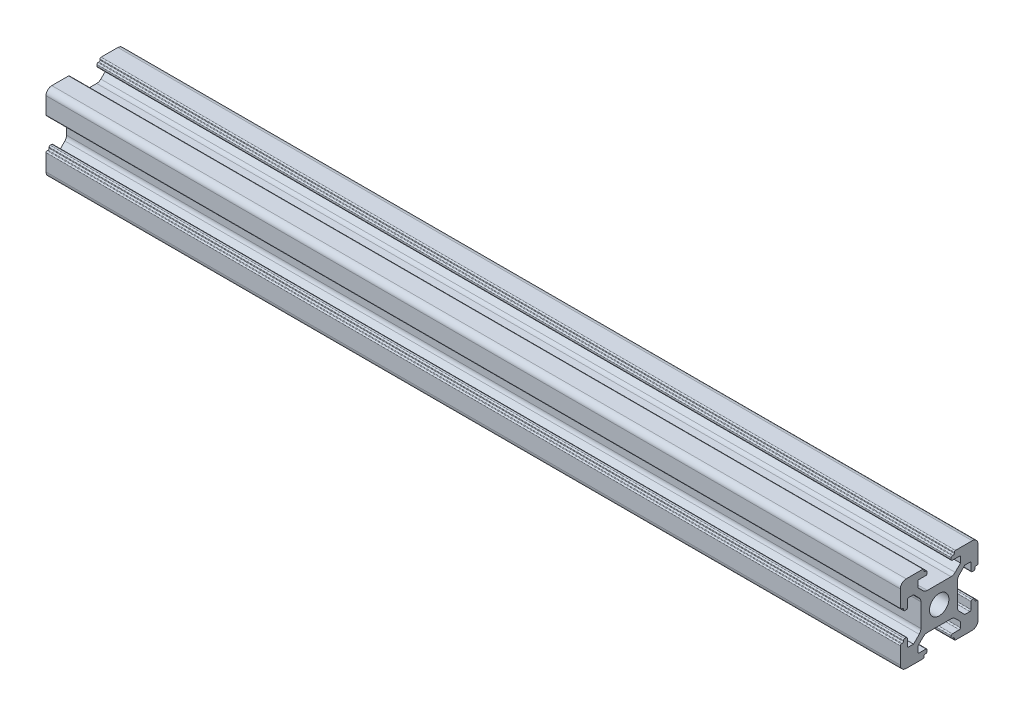
SolidWorks part; units mm, degrees
ref_plane "Front Plane" through (0, 0, 0) normal (0, 0, 1) x (1, 0, 0)
ref_plane "Top Plane" through (0, 0, 0) normal (0, 1, 0) x (1, 0, 0)
ref_plane "Right Plane" through (0, 0, 0) normal (1, 0, 0) x (0, 0, -1)
sketch "Sketch1" plane through (0, 0, 0) normal (1, 0, 0) x (0, 0, -1)
  line L0 (0, 0) -> (0, 50000) construction
  line L1 (0, 0) -> (-50000, 0) construction
  line L2 (10, 4.2) -> (10, 8.5)
  line L3 (9.7, 3.9) -> (9.5, 3.9)
  line L4 (9.2, 3.6) -> (9.2, 3.4)
  line L5 (8.9, 3.1) -> (8.5, 3.1)
  line L6 (8.2, 3.4) -> (8.2, 5.2)
  line L7 (7.9, 5.5) -> (6.6, 5.5)
  line L8 (6.6, 5.5) -> (5.1393, 4.0393)
  line L9 (8.5, 10) -> (4.2, 10)
  line L10 (3.9, 9.7) -> (3.9, 9.5)
  line L11 (3.6, 9.2) -> (3.4, 9.2)
  line L12 (3.1, 8.9) -> (3.1, 8.5)
  line L13 (3.4, 8.2) -> (5.2, 8.2)
  line L14 (5.5, 7.9) -> (5.5, 6.5213)
  line L15 (5.5, 6.5213) -> (4.118, 5.1393)
  line L16 (4.7, 2.9787) -> (4.7, -2.9787)
  line L17 (3.0574, 4.7) -> (-3.0574, 4.7)
  line L18 (-4.7, 2.9787) -> (-4.7, -2.9787)
  line L19 (-5.5, 6.5213) -> (-4.118, 5.1393)
  line L20 (-5.5, 7.9) -> (-5.5, 6.5213)
  line L21 (-3.4, 8.2) -> (-5.2, 8.2)
  line L22 (-3.1, 8.9) -> (-3.1, 8.5)
  line L23 (-3.6, 9.2) -> (-3.4, 9.2)
  line L24 (-3.9, 9.7) -> (-3.9, 9.5)
  line L25 (-8.5, 10) -> (-4.2, 10)
  line L26 (-6.6, 5.5) -> (-5.1393, 4.0393)
  line L27 (-7.9, 5.5) -> (-6.6, 5.5)
  line L28 (-8.2, 3.4) -> (-8.2, 5.2)
  line L29 (-8.9, 3.1) -> (-8.5, 3.1)
  line L30 (-9.2, 3.6) -> (-9.2, 3.4)
  line L31 (-9.7, 3.9) -> (-9.5, 3.9)
  line L32 (-10, 4.2) -> (-10, 8.5)
  line L33 (-10, -4.2) -> (-10, -8.5)
  line L34 (-9.7, -3.9) -> (-9.5, -3.9)
  line L35 (-9.2, -3.6) -> (-9.2, -3.4)
  line L36 (-8.9, -3.1) -> (-8.5, -3.1)
  line L37 (-8.2, -3.4) -> (-8.2, -5.2)
  line L38 (-7.9, -5.5) -> (-6.6, -5.5)
  line L39 (-6.6, -5.5) -> (-5.1393, -4.0393)
  line L40 (-8.5, -10) -> (-4.2, -10)
  line L41 (-3.9, -9.7) -> (-3.9, -9.5)
  line L42 (-3.6, -9.2) -> (-3.4, -9.2)
  line L43 (-3.1, -8.9) -> (-3.1, -8.5)
  line L44 (-3.4, -8.2) -> (-5.2, -8.2)
  line L45 (-5.5, -7.9) -> (-5.5, -6.5213)
  line L46 (-5.5, -6.5213) -> (-4.118, -5.1393)
  line L47 (3.0574, -4.7) -> (-3.0574, -4.7)
  line L48 (5.5, -6.5213) -> (4.118, -5.1393)
  line L49 (5.5, -7.9) -> (5.5, -6.5213)
  line L50 (3.4, -8.2) -> (5.2, -8.2)
  line L51 (3.1, -8.9) -> (3.1, -8.5)
  line L52 (3.6, -9.2) -> (3.4, -9.2)
  line L53 (3.9, -9.7) -> (3.9, -9.5)
  line L54 (8.5, -10) -> (4.2, -10)
  line L55 (6.6, -5.5) -> (5.1393, -4.0393)
  line L56 (7.9, -5.5) -> (6.6, -5.5)
  line L57 (8.2, -3.4) -> (8.2, -5.2)
  line L58 (8.9, -3.1) -> (8.5, -3.1)
  line L59 (9.2, -3.6) -> (9.2, -3.4)
  line L60 (9.7, -3.9) -> (9.5, -3.9)
  line L61 (10, -4.2) -> (10, -8.5)
  circle A0 centre (0, 0) radius 2.5
  arc A1 (10, 8.5) -> (8.5, 10) centre (8.5, 8.5) ccw
  arc A2 (9.7, 3.9) -> (10, 4.2) centre (9.7, 4.2) ccw
  arc A3 (9.5, 3.9) -> (9.2, 3.6) centre (9.5, 3.6) ccw
  arc A4 (9.2, 3.4) -> (8.9, 3.1) centre (8.9, 3.4) cw
  arc A5 (8.5, 3.1) -> (8.2, 3.4) centre (8.5, 3.4) cw
  arc A6 (8.2, 5.2) -> (7.9, 5.5) centre (7.9, 5.2) ccw
  arc A7 (5.2, 8.2) -> (5.5, 7.9) centre (5.2, 7.9) cw
  arc A8 (3.1, 8.5) -> (3.4, 8.2) centre (3.4, 8.5) ccw
  arc A9 (3.4, 9.2) -> (3.1, 8.9) centre (3.4, 8.9) ccw
  arc A10 (4.2, 10) -> (3.9, 9.7) centre (4.2, 9.7) ccw
  arc A11 (3.9, 9.5) -> (3.6, 9.2) centre (3.6, 9.5) cw
  arc A12 (4.7, 2.9787) -> (5.1393, 4.0393) centre (6.2, 2.9787) cw
  arc A13 (3.0574, 4.7) -> (4.118, 5.1393) centre (3.0574, 6.2) ccw
  arc A14 (-3.0574, 4.7) -> (-4.118, 5.1393) centre (-3.0574, 6.2) cw
  arc A15 (-4.7, 2.9787) -> (-5.1393, 4.0393) centre (-6.2, 2.9787) ccw
  arc A16 (-3.9, 9.5) -> (-3.6, 9.2) centre (-3.6, 9.5) ccw
  arc A17 (-4.2, 10) -> (-3.9, 9.7) centre (-4.2, 9.7) cw
  arc A18 (-3.4, 9.2) -> (-3.1, 8.9) centre (-3.4, 8.9) cw
  arc A19 (-3.1, 8.5) -> (-3.4, 8.2) centre (-3.4, 8.5) cw
  arc A20 (-5.2, 8.2) -> (-5.5, 7.9) centre (-5.2, 7.9) ccw
  arc A21 (-8.2, 5.2) -> (-7.9, 5.5) centre (-7.9, 5.2) cw
  arc A22 (-8.5, 3.1) -> (-8.2, 3.4) centre (-8.5, 3.4) ccw
  arc A23 (-9.2, 3.4) -> (-8.9, 3.1) centre (-8.9, 3.4) ccw
  arc A24 (-9.5, 3.9) -> (-9.2, 3.6) centre (-9.5, 3.6) cw
  arc A25 (-9.7, 3.9) -> (-10, 4.2) centre (-9.7, 4.2) cw
  arc A26 (-10, 8.5) -> (-8.5, 10) centre (-8.5, 8.5) cw
  arc A27 (-10, -8.5) -> (-8.5, -10) centre (-8.5, -8.5) ccw
  arc A28 (-9.7, -3.9) -> (-10, -4.2) centre (-9.7, -4.2) ccw
  arc A29 (-9.5, -3.9) -> (-9.2, -3.6) centre (-9.5, -3.6) ccw
  arc A30 (-9.2, -3.4) -> (-8.9, -3.1) centre (-8.9, -3.4) cw
  arc A31 (-8.5, -3.1) -> (-8.2, -3.4) centre (-8.5, -3.4) cw
  arc A32 (-8.2, -5.2) -> (-7.9, -5.5) centre (-7.9, -5.2) ccw
  arc A33 (-5.2, -8.2) -> (-5.5, -7.9) centre (-5.2, -7.9) cw
  arc A34 (-3.1, -8.5) -> (-3.4, -8.2) centre (-3.4, -8.5) ccw
  arc A35 (-3.4, -9.2) -> (-3.1, -8.9) centre (-3.4, -8.9) ccw
  arc A36 (-4.2, -10) -> (-3.9, -9.7) centre (-4.2, -9.7) ccw
  arc A37 (-3.9, -9.5) -> (-3.6, -9.2) centre (-3.6, -9.5) cw
  arc A38 (-4.7, -2.9787) -> (-5.1393, -4.0393) centre (-6.2, -2.9787) cw
  arc A39 (-3.0574, -4.7) -> (-4.118, -5.1393) centre (-3.0574, -6.2) ccw
  arc A40 (3.0574, -4.7) -> (4.118, -5.1393) centre (3.0574, -6.2) cw
  arc A41 (4.7, -2.9787) -> (5.1393, -4.0393) centre (6.2, -2.9787) ccw
  arc A42 (3.9, -9.5) -> (3.6, -9.2) centre (3.6, -9.5) ccw
  arc A43 (4.2, -10) -> (3.9, -9.7) centre (4.2, -9.7) cw
  arc A44 (3.4, -9.2) -> (3.1, -8.9) centre (3.4, -8.9) cw
  arc A45 (3.1, -8.5) -> (3.4, -8.2) centre (3.4, -8.5) cw
  arc A46 (5.2, -8.2) -> (5.5, -7.9) centre (5.2, -7.9) ccw
  arc A47 (8.2, -5.2) -> (7.9, -5.5) centre (7.9, -5.2) cw
  arc A48 (8.5, -3.1) -> (8.2, -3.4) centre (8.5, -3.4) ccw
  arc A49 (9.2, -3.4) -> (8.9, -3.1) centre (8.9, -3.4) ccw
  arc A50 (9.5, -3.9) -> (9.2, -3.6) centre (9.5, -3.6) cw
  arc A51 (9.7, -3.9) -> (10, -4.2) centre (9.7, -4.2) cw
  arc A52 (10, -8.5) -> (8.5, -10) centre (8.5, -8.5) cw
  point P24 (10, 10)
  point P41 (3.1, 9.2)
  point P44 (3.9, 10)
  point P94 (4.7, 0)
  point P95 (0, 4.7)
  point P175 (0, -4.7)
  point P176 (-4.7, 0)
  dimension "D1" = 5
  dimension "D15" = 1.5
  dimension "D16" = 0.3
  dimension "D19" = 1.5
  dimension "D2" = 20
  dimension "D3" = 1.8
  dimension "D4" = 6.2
  dimension "D5" = 3.4
  dimension "D6" = 11
  dimension "D7" = 6.1
  dimension "D8" = 1.5
  dimension "D9" = 20
  dimension "D10" = 6.1
  dimension "D11" = 6.2
  dimension "D12" = 11
  dimension "D13" = 45
  dimension "D14" = 1.8
  dimension "D17" = 3.5
  dimension "D18" = 3.5
extrude "Boss-Extrude2" add sketch "Sketch1" along normal mid plane 220
